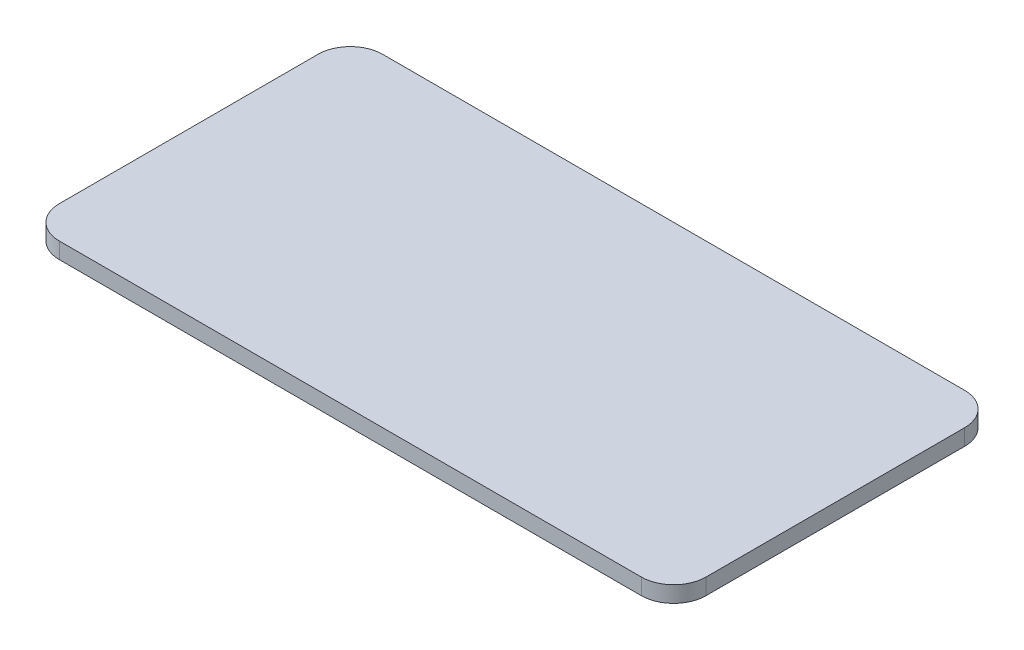
SolidWorks part; units mm, degrees
ref_plane "Front Plane" through (0, 0, 0) normal (0, 0, 1) x (1, 0, 0)
ref_plane "Top Plane" through (0, 0, 0) normal (0, 1, 0) x (1, 0, 0)
ref_plane "Right Plane" through (0, 0, 0) normal (1, 0, 0) x (0, 0, -1)
sketch "Sketch1" plane through (0, 0, 0) normal (0, 1, 0) x (1, 0, 0)
  line L1 (-20, -10) -> (20, -10)
  line L2 (-20, -10) -> (-20, 10)
  line L3 (-20, 10) -> (20, 10)
  line L4 (20, -10) -> (20, 10)
  line L5 (-20, -10) -> (20, 10) construction
  line L6 (-20, 10) -> (20, -10) construction
  point P0 (0, 0)
  dimension "D1" = 20
  dimension "D2" = 40
extrude "Boss-Extrude1" add sketch "Sketch1" along normal mid plane 1
fillet "Fillet1" radius 2 4 edges at (-20, 0, -10) (20, 0, -10) (-20, 0, 10) (20, 0, 10)
